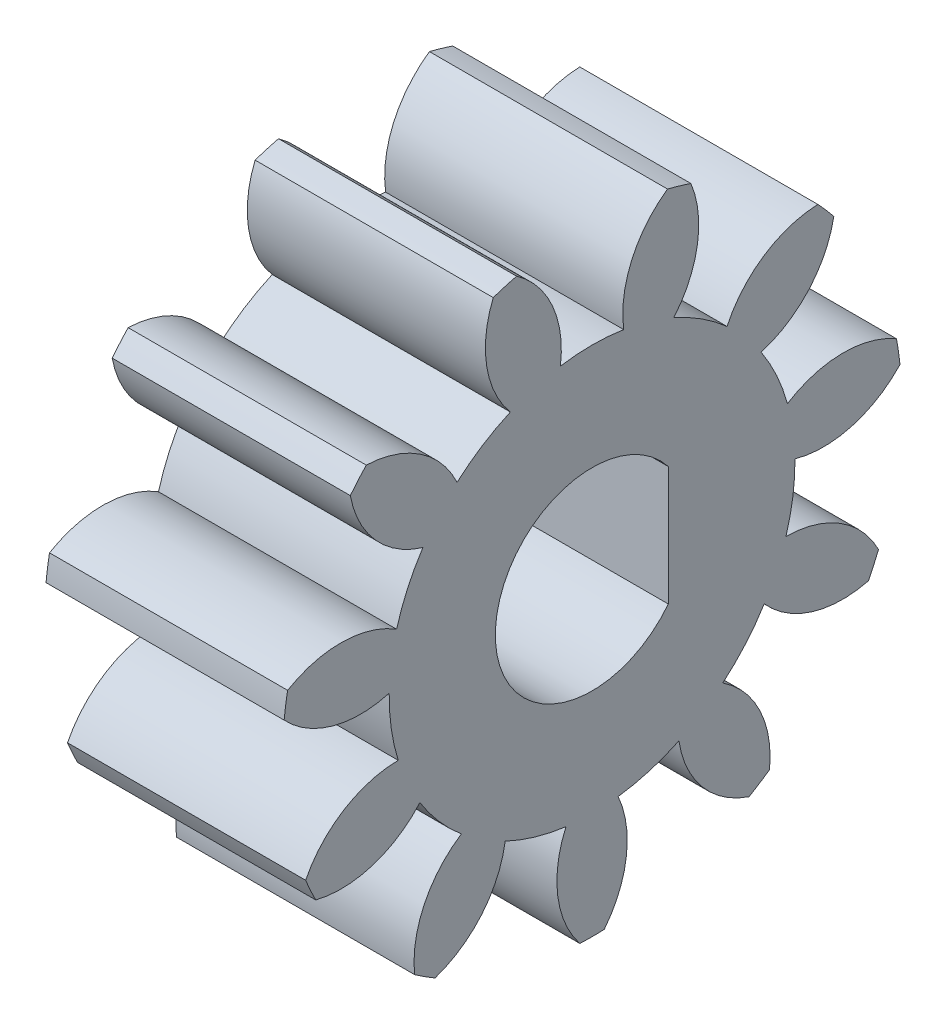
SolidWorks part; units mm, degrees
ref_plane "Plane1" through (0, 0, 0) normal (0, 0, 1) x (1, 0, 0)
ref_plane "Plane2" through (0, 0, 0) normal (0, 1, 0) x (1, 0, 0)
ref_plane "Plane3" through (0, 0, 0) normal (1, 0, 0) x (0, 0, -1)
sketch "HoldingSke" plane through (0, 0, 0) normal (0, 1, 0) x (1, 0, 0)
  line L0 (0, 0) -> (498.6666, -96.931)
  line L1 (-15, 0) -> (100, 0) construction
  line L2 (0, 0) -> (-2.1039, 2.3779)
  line L3 (0, 0) -> (-11.863, 4.5341)
  line L4 (0, 0) -> (8.4773, 1.6478)
  line L5 (0, 0) -> (-47.5972, -17.7524)
  line L6 (0, 0) -> (-5.2639, -3.5516)
  line L7 (-2.1039, 2.3779) -> (8.8308, 51.9871)
  line L8 (-76.2, 54.61) -> (-72.771, 54.61)
  line L9 (-67.7845, 28.3722) -> (-49.3413, 33.142)
  line L10 (-76.2, 71.12) -> (104.1128, 71.12)
  line L11 (0, 0) -> (-6.35, 0)
  line L12 (-76.2, 101.6) -> (-76.1492, 101.6)
  line L13 (24.9733, 27.94) -> (52.9518, 28.4284)
  line L14 (24.9733, 27.94) -> (25.0241, 27.9398)
  line L15 (24.9733, 27.94) -> (100.4021, 29.52)
  circle A0 centre (0, 0) radius 1.5875
  circle A1 centre (0, 0) radius 5.4102
  circle A2 centre (0, 0) radius 38.1
  circle A3 centre (0, 0) radius 1.5875
  dimension "MHD" = 10.8204
  dimension "Hub_dia" = 76.2
  dimension "Bore" = 3.175
  dimension "MBD" = 3.175
  dimension "Num_teeth" = 11
  dimension "Pitch" = 508
  dimension "Overall_len" = 50.8
  dimension "Show_teeth" = 11
  dimension "Thickness" = 6.35
  dimension "OAL" = 50.8001
  dimension "T_dim" = 3.429
  dimension "Ap" = 14.5
  dimension "H" = 19.05
  dimension "Pitch_radius" = 180.3128
  dimension "Width" = 6.35
  dimension "Backlash" = 0.0508
  dimension "Addendum_fac" = 1
  dimension "Dedendum_fac" = 1.2
  dimension "Clearance_fac" = 0.2
  dimension "Dedendum_add" = 0.0508
sketch "BasProSke" plane through (0, 0, 0) normal (0, 1, 0) x (1, 0, 0)
  line L0 (-10, 0) -> (60, 0) construction
  line L1 (0, 0) -> (0, 8.255)
  line L2 (0, 0) -> (6.35, 0)
  line L3 (6.35, 0) -> (6.35, 8.255)
  line L4 (6.35, 8.255) -> (0, 8.255)
  dimension "Thickness" = 6.35
  dimension "Diameter" = 16.51
revolve "Base-Revolve" add sketch "BasProSke" angle 360 about L0
sketch "TooCutSke" plane through (0, 0, 0) normal (1, 0, 0) x (0, 0, -1)
  line L1 (0, 0) -> (0, 107) construction
  line L2 (0, 0) -> (-1.0828, 6.9006) construction
  line L3 (0, 0) -> (-3.9026, 13.2911) construction
  line L4 (-1.0828, 6.9006) -> (-1.9513, 6.6455) construction
  arc A0 (0.8443, 5.3439) -> (-0.8443, 5.3439) centre (0, 0) ccw
  arc A1 (2.0401, 8.0252) -> (-2.0401, 8.0252) centre (0, 0) ccw
  circle A2 centre (0, 0) radius 6.985 construction
  circle A3 centre (0, 0) radius 6.7625 construction
  arc A4 (-0.8443, 5.3439) -> (-2.0401, 8.0252) centre (-3.6134, 5.7162) ccw
  arc A5 (2.0401, 8.0252) -> (0.8443, 5.3439) centre (3.6134, 5.7162) ccw
  dimension "Root_dia" = 10.8204
  dimension "Overcut_dia" = 16.5608
  dimension "Pitch_dia" = 13.97
  dimension "Base_dia" = 13.525
  dimension "Flank_rad" = 2.794
  dimension "Half_ang" = 16.364
  dimension "Half_CT" = 0.9052
extrude "ToothCut" cut sketch "TooCutSke" along normal through all
fillet "Breaks" [suppressed] radius 0.0254
fillet "RootFillets" [suppressed] radius 0.3048
pattern_circular "TeethCuts" count 11 every 32.727 about axis through (-10, 0, 0) along (1, 0, 0) of "ToothCut", "RootFillets", "Breaks"
sketch "HubNeaOneSke" plane through (0, 0, 0) normal (-1, 0, 0) x (0, 0, 1)
  circle A0 centre (0, 0) radius 5.4102
  dimension "Diameter" = 10.8204
extrude "HubNearOne" [suppressed] add sketch "HubNeaOneSke" along normal blind 44.4501
sketch "HubNeaBotSke" plane through (0, 0, 0) normal (-1, 0, 0) x (0, 0, 1)
  circle A0 centre (0, 0) radius 5.4102
  dimension "Diameter" = 10.8204
extrude "HubNearBoth" [suppressed] add sketch "HubNeaBotSke" along normal blind 22.225
ref_plane "FarPln" through (6.35, 0, 0) normal (1, 0, 0) x (0, 0, -1)
sketch "HubFarSke" plane through (6.35, 0, 0) normal (1, 0, 0) x (0, 0, -1)
  circle A0 centre (0, 0) radius 5.4102
  dimension "Diameter" = 10.8204
extrude "HubFar" [suppressed] add sketch "HubFarSke" along normal blind 22.225
sketch "BorSke" plane through (0, 0, 0) normal (1, 0, 0) x (0, 0, -1)
  circle A0 centre (0, 0) radius 1.5875
  dimension "Diameter" = 3.175
extrude "Bore" cut sketch "BorSke" along normal mid plane 101.6001
sketch "KeySke" plane through (0, 0, 0) normal (1, 0, 0) x (0, 0, -1)
  line L0 (-0.127, 0) -> (-0.127, 1.8415)
  line L1 (-0.127, 1.8415) -> (0.127, 1.8415)
  line L2 (0.127, 1.8415) -> (0.127, 0)
  line L3 (0, 0) -> (0, 34) construction
  line L4 (-0.127, 0) -> (0.127, 0)
  dimension "Offset" = 1.8415
  dimension "Width" = 0.254
extrude "Keyway" [suppressed] cut sketch "KeySke" along normal mid plane 101.6001
pattern_circular "Keyway2" [suppressed] count 2 every 90 about axis through (-10, 0, 0) along (1, 0, 0)
sketch "Sketch1" plane through (6.35, 0, 0) normal (1, 0, 0) x (0, 0, -1)
  line L0 (2.5797, 0) -> (3.094, 0) construction
  line L1 (3.094, -1.5875) -> (3.094, 1.5875) construction
  line L2 (3.094, 1.5875) -> (2.0334, 1.5875) construction
  line L3 (2.0334, 1.5875) -> (2.0334, -1.5875)
  circle A0 centre (0, 0) radius 2.5797
  point P9 (3.094, 0)
  circle M3 centre (0, 0) radius 1.5875
  dimension "D1" = 5.1594
  dimension "D2" = 3.175
extrude "Cut-Extrude1" cut sketch "Sketch1" against normal through all contours L3 A0 M3
equation "' \"Pitch@HoldingSke\" = 4"
equation "' \"Num_teeth@HoldingSke\" = 12"
equation "' \"Ap@HoldingSke\" =  20"
equation "' \"Ap@HoldingSke\" = 20"
equation "' \"Width@HoldingSke\" = 0.5"
equation "' \"Hub_dia@HoldingSke\"= 1"
equation "' \"Hub_dia@HoldingSke\" = 1"
equation "' \"Overall_len@HoldingSke\" = 1.0"
equation "' \"Bore@HoldingSke\" = 0.75"
equation "' \"T_dim@HoldingSke\" = 0.85"
equation "' \"Width@KeySke\" = 0.25"
equation "' \"Show_teeth@HoldingSke\" = 13"
equation "' \"Backlash@HoldingSke\" = 0.009"
equation "' \"Addendum_fac@HoldingSke\" = 1.0"
equation "' \"Dedendum_fac@HoldingSke\" = 1.25"
equation "' \"Dedendum_add@HoldingSke\" = 0.00005"
equation "' \"Clearance_fac@HoldingSke\" = 0.25"
equation "' \"Pitch@HoldingSke\" = 0.5"
equation "' \"Num_teeth@HoldingSke\" = 23"
equation "' \"Show_teeth@HoldingSke\" = 23"
equation "' \"Backlash@HoldingSke\" = 0.0375"
equation "\"Overcut_dia@TooCutSke\" = (\"Num_teeth@HoldingSke\" + 2 * \"Addendum_fac@HoldingSke\") / \"Pitch@HoldingSke\" + 0.002"
equation "\"Pitch_dia@TooCutSke\" = \"Num_teeth@HoldingSke\" / \"Pitch@HoldingSke\""
equation "\"Base_dia@TooCutSke\" = \"Num_teeth@HoldingSke\" / \"Pitch@HoldingSke\" * cos((\"Ap@HoldingSke\"  * 3.14159265 / 180))"
equation "\"Root_dia@TooCutSke\" = (\"Num_teeth@HoldingSke\" + 2) / \"Pitch@HoldingSke\" - 2 * (\"Addendum_fac@HoldingSke\" + \"Dedendum_fac@HoldingSke\") / \"Pitch@HoldingSke\" - \"Dedendum_add@HoldingSke\" * 2"
equation "\"Half_ang@TooCutSke\" = 180 / \"Num_teeth@HoldingSke\""
equation "\"Half_CT@TooCutSke\" = \"Num_teeth@HoldingSke\" / \"Pitch@HoldingSke\" * sin((3.14159265 / 2 / \"Num_teeth@HoldingSke\")) / 2 - 7 * \"Backlash@HoldingSke\" / 4"
equation "\"Flank_rad@TooCutSke\" = \"Num_teeth@HoldingSke\" / \"Pitch@HoldingSke\" / 5"
equation "\"Radius@RootFillets\" = \"Clearance_fac@HoldingSke\" / \"Pitch@HoldingSke\" + \"Dedendum_add@HoldingSke\""
equation "\"Break_rad@Breaks\" = 0.02 / \"Pitch@HoldingSke\""
equation "\"Thickness@HoldingSke\" = \"Width@HoldingSke\""
equation "\"OAL@HoldingSke\" = \"Thickness@HoldingSke\""
equation "\"MHD@HoldingSke\" = (\"Num_teeth@HoldingSke\" + 2) / \"Pitch@HoldingSke\" - 2 * (\"Addendum_fac@HoldingSke\" + \"Dedendum_fac@HoldingSke\")  / \"Pitch@HoldingSke\" - \"Dedendum_add@HoldingSke\" * 2"
equation "\"MBD@HoldingSke\" = (\"Num_teeth@HoldingSke\" + 2) / \"Pitch@HoldingSke\" - 2 * (\"Addendum_fac@HoldingSke\" + \"Dedendum_fac@HoldingSke\")  / \"Pitch@HoldingSke\" - \"Dedendum_add@HoldingSke\" * 2 - 0.002"
equation "\"MHD@HoldingSke\" = ((sgn( \"MHD@HoldingSke\" - \"Hub_dia@HoldingSke\" )-1)*( \"MHD@HoldingSke\" - \"Hub_dia@HoldingSke\" ))/-2+ \"Hub_dia@HoldingSke\""
equation "\"MBD@HoldingSke\" = ((sgn( \"MBD@HoldingSke\" - \"Bore@HoldingSke\" )-1)*( \"MBD@HoldingSke\" - \"Bore@HoldingSke\" ))/-2+ \"Bore@HoldingSke\""
equation "\"OAL@HoldingSke\" = ((sgn( \"OAL@HoldingSke\" - \"Overall_len@HoldingSke\" )+1)*( \"OAL@HoldingSke\" - \"Overall_len@HoldingSke\" ))/2 + \"Overall_len@HoldingSke\" + 0.000002"
equation "\"Num_teeth@TeethCuts\" = int( \"Show_teeth@HoldingSke\" ) + 1"
equation "\"Num_teeth@TeethCuts\" = ((sgn( \"Num_teeth@TeethCuts\" - \"Num_teeth@HoldingSke\" )-1)*( \"Num_teeth@TeethCuts\" - \"Num_teeth@HoldingSke\" ))/-2+ \"Num_teeth@HoldingSke\""
equation "\"Num_teeth@TeethCuts\" = ((sgn( \"Num_teeth@TeethCuts\" - 2.0)+1)*( \"Num_teeth@TeethCuts\" - 2.0))/2 +2.0"
equation "\"Angle@TeethCuts\" = 360.0 / \"Num_teeth@HoldingSke\""
equation "\"Diameter@BasProSke\" = (\"Num_teeth@HoldingSke\" + 2 * \"Addendum_fac@HoldingSke\") / \"Pitch@HoldingSke\""
equation "\"Thickness@BasProSke\"  = \"Thickness@HoldingSke\""
equation "' \"Fillet_rad@BasProSke\" =  \"Thickness@HoldingSke\" * 0.05"
equation "' \"Fillet_rad@BasProSke\" = \"Thickness@HoldingSke\" * 0.05"
equation "\"MHD@HoldingSke\" = ((sgn( \"MHD@HoldingSke\" - \"Root_dia@TooCutSke\" )-1)*( \"MHD@HoldingSke\" - \"Root_dia@TooCutSke\" ))/-2+ \"Root_dia@TooCutSke\""
equation "\"Diameter@HubNeaOneSke\" = \"MHD@HoldingSke\""
equation "\"Length@HubNearOne\" = \"OAL@HoldingSke\" - \"Thickness@BasProSke\""
equation "\"Diameter@HubNeaBotSke\" = \"MHD@HoldingSke\""
equation "\"Length@HubNearBoth\" = ( \"OAL@HoldingSke\" - \"Thickness@BasProSke\" ) / 2.0"
equation "\"Thickness@FarPln\" = \"Thickness@BasProSke\""
equation "\"Diameter@HubFarSke\" = \"MHD@HoldingSke\""
equation "\"Length@HubFar\" = ( \"OAL@HoldingSke\" - \"Thickness@BasProSke\" ) / 2.0"
equation "\"Diameter@BorSke\" = \"MBD@HoldingSke\""
equation "\"D1@Bore\" = \"OAL@HoldingSke\" * 2.0"
equation "\"D1@Keyway\" = \"OAL@HoldingSke\" * 2.0"
equation "\"Offset@KeySke\" = \"T_dim@HoldingSke\" - \"MBD@HoldingSke\" / 2.0"
